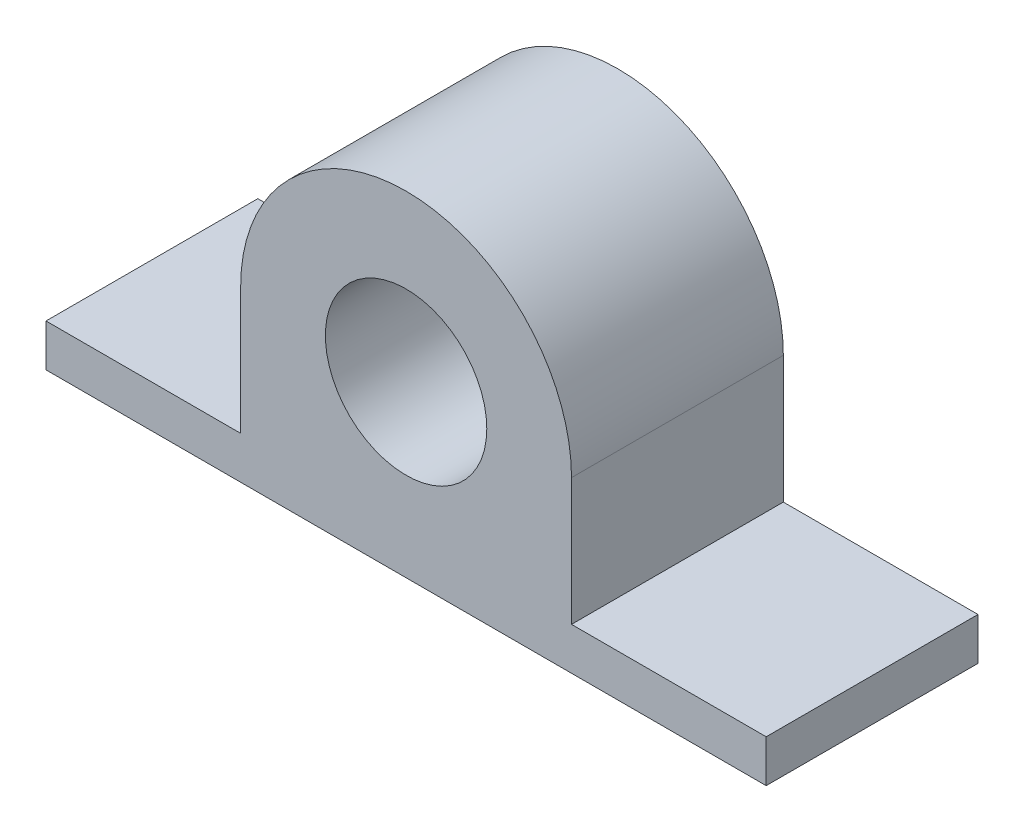
SolidWorks part; units mm, degrees
ref_plane "Front Plane" through (0, 0, 0) normal (0, 0, 1) x (1, 0, 0)
ref_plane "Top Plane" through (0, 0, 0) normal (0, 1, 0) x (1, 0, 0)
ref_plane "Right Plane" through (0, 0, 0) normal (1, 0, 0) x (0, 0, -1)
sketch "Sketch1" plane through (0, 0, 0) normal (0, 0, 1) x (1, 0, 0)
  line L0 (-19.525, 0) -> (-19.525, -15)
  line L5 (-42.5, -15) -> (-19.525, -15)
  line L6 (-42.5, -15) -> (-42.5, -20)
  line L7 (-42.5, -20) -> (42.5, -20)
  line L8 (42.5, -15) -> (42.5, -20)
  line L9 (19.525, 0) -> (19.525, -15)
  line L10 (19.525, -15) -> (42.5, -15)
  circle A0 centre (0, 0) radius 9.525
  arc A1 (19.525, 0) -> (-19.525, 0) centre (0, 0) ccw
  circle A2 centre (0, 0) radius 19.525 construction
  point P4 (0, 0)
  point P9 (0, -20)
  dimension "D1" = 19.05
  dimension "D2" = 10
  dimension "D3" = 85
  dimension "D4" = 5
  dimension "D5" = 20
extrude "Boss-Extrude1" add sketch "Sketch1" along normal mid plane 25
